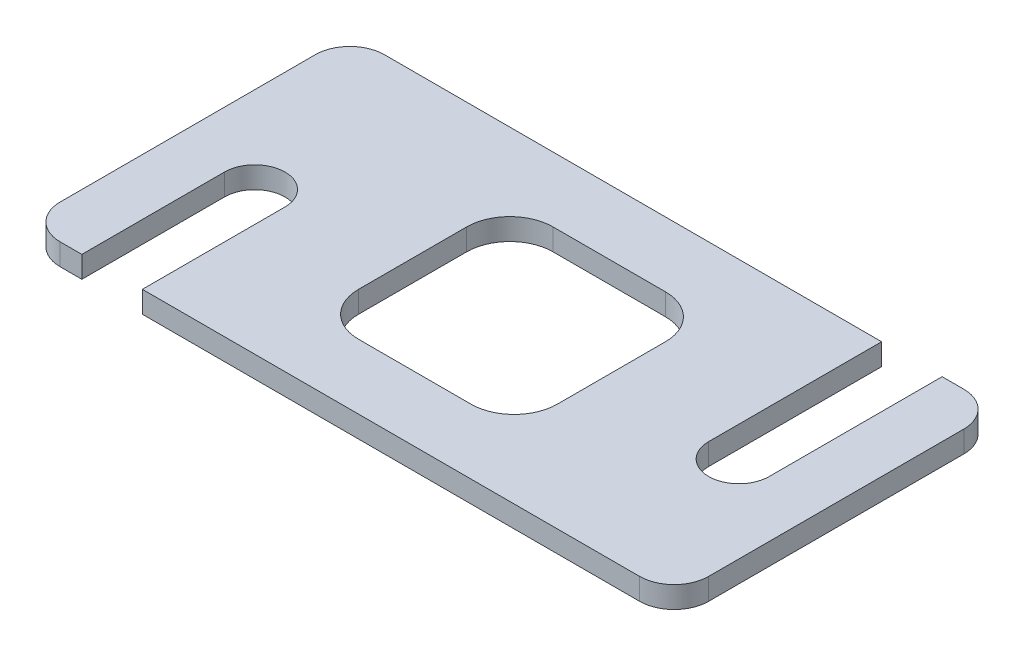
SolidWorks part; units mm, degrees
ref_plane "Front Plane" through (0, 0, 0) normal (0, 0, 1) x (1, 0, 0)
ref_plane "Top Plane" through (0, 0, 0) normal (0, 1, 0) x (1, 0, 0)
ref_plane "Right Plane" through (0, 0, 0) normal (1, 0, 0) x (0, 0, -1)
sketch "Sketch1" plane through (0, 0, 0) normal (0, 1, 0) x (1, 0, 0)
  line L1 (0, 0) -> (150, 0)
  line L2 (0, 0) -> (0, 75)
  line L3 (0, 75) -> (150, 75)
  line L4 (150, 0) -> (150, 75)
  dimension "D1" = 150
  dimension "D2" = 75
extrude "Boss-Extrude1" add sketch "Sketch1" along normal blind 5
sketch "Sketch2" plane through (0, 5, 0) normal (0, 1, 0) x (1, 0, 0)
  line L0 (13, 0) -> (13, 33)
  line L1 (0, 0) -> (150, 0) construction
  line L2 (27, 0) -> (13, 0)
  line L3 (27, 33) -> (27, 0)
  line L4 (0, 75) -> (0, 0) construction
  arc A0 (13, 33) -> (27, 33) centre (20, 33) cw
  point P6 (20, 40)
  dimension "D1" = 40
  dimension "D3" = 7
  dimension "D2" = 20
extrude "Cut-Extrude1" cut sketch "Sketch2" against normal through all
sketch "Sketch3" plane through (0, 5, 0) normal (0, 1, 0) x (1, 0, 0)
  line L0 (137, 75) -> (137, 35)
  line L1 (150, 75) -> (0, 75) construction
  line L2 (123, 35) -> (123, 75)
  line L3 (123, 75) -> (137, 75)
  line L4 (150, 0) -> (150, 75) construction
  arc A0 (137, 35) -> (123, 35) centre (130, 35) cw
  dimension "D3" = 7
  dimension "D1" = 40
  dimension "D2" = 20
extrude "Cut-Extrude2" cut sketch "Sketch3" against normal through all
sketch "Sketch4" plane through (0, 5, 0) normal (0, 1, 0) x (1, 0, 0)
  line L0 (27, 0) -> (27, 33) construction
  line L1 (52, 15) -> (98, 15)
  line L2 (52, 15) -> (52, 60)
  line L3 (52, 60) -> (98, 60)
  line L4 (98, 15) -> (98, 60)
  line L5 (123, 75) -> (123, 35) construction
  line L6 (123, 75) -> (0, 75) construction
  line L7 (27, 0) -> (150, 0) construction
  dimension "D1" = 25
  dimension "D2" = 25
  dimension "D3" = 15
  dimension "D4" = 15
extrude "Cut-Extrude3" cut sketch "Sketch4" against normal through all
fillet "Fillet1" radius 10 4 edges at (52, 2.5, -60) (52, 2.5, -15) (98, 2.5, -15) (98, 2.5, -60)
fillet "Fillet2" radius 8 4 edges at (150, 2.5, 0) (0, 2.5, -75) (0, 2.5, 0) (150, 2.5, -75)
